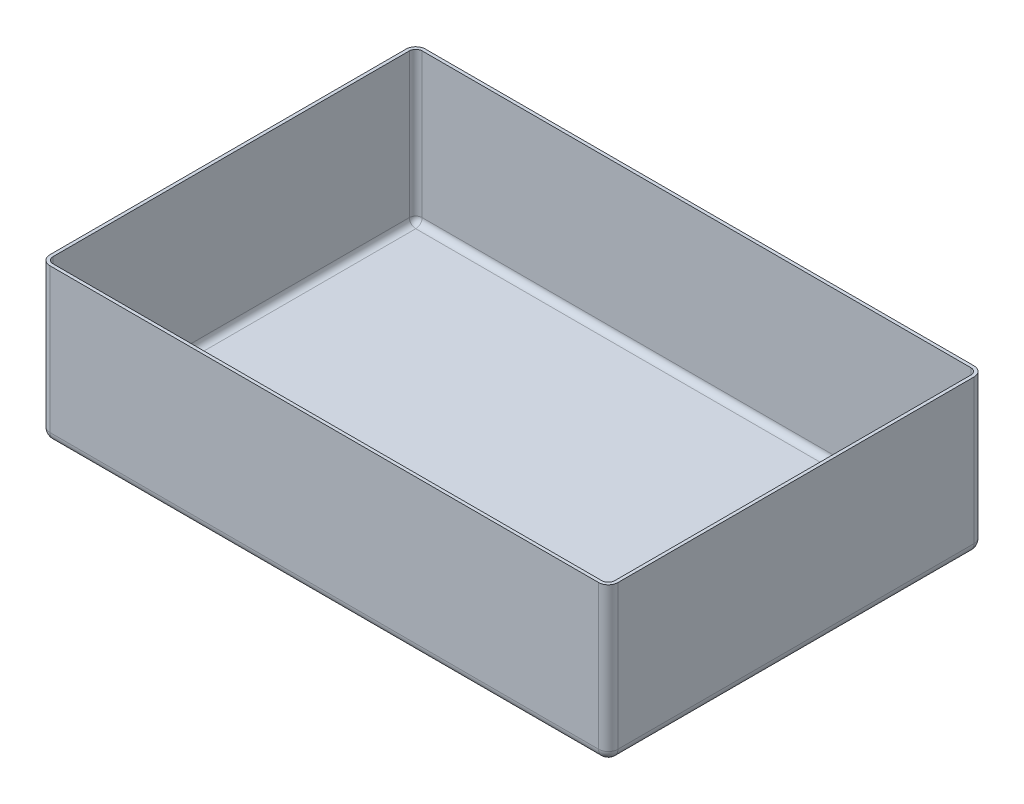
SolidWorks part; units mm, degrees
ref_plane "Front Plane" through (0, 0, 0) normal (0, 0, 1) x (1, 0, 0)
ref_plane "Top Plane" through (0, 0, 0) normal (0, 1, 0) x (1, 0, 0)
ref_plane "Right Plane" through (0, 0, 0) normal (1, 0, 0) x (0, 0, -1)
sketch "Sketch1" plane through (0, 0, 0) normal (0, 1, 0) x (1, 0, 0)
  line L1 (-66.2482, 35.0841) -> (110.7518, 35.0841)
  line L2 (-66.2482, 35.0841) -> (-66.2482, -81.9159)
  line L3 (-66.2482, -81.9159) -> (110.7518, -81.9159)
  line L4 (110.7518, 35.0841) -> (110.7518, -81.9159)
  dimension "D1" = 177
  dimension "D2" = 117
extrude "Boss-Extrude1" add sketch "Sketch1" along normal blind 48
fillet "Fillet2" radius 3 8 edges at (110.7518, 0, 23.4159) (22.2518, 0, 81.9159) (22.2518, 0, -35.0841) (-66.2482, 0, 23.4159) (110.7518, 24, -35.0841) (110.7518, 24, 81.9159) (-66.2482, 24, 81.9159) (-66.2482, 24, -35.0841)
shell "Shell1" thickness 1
